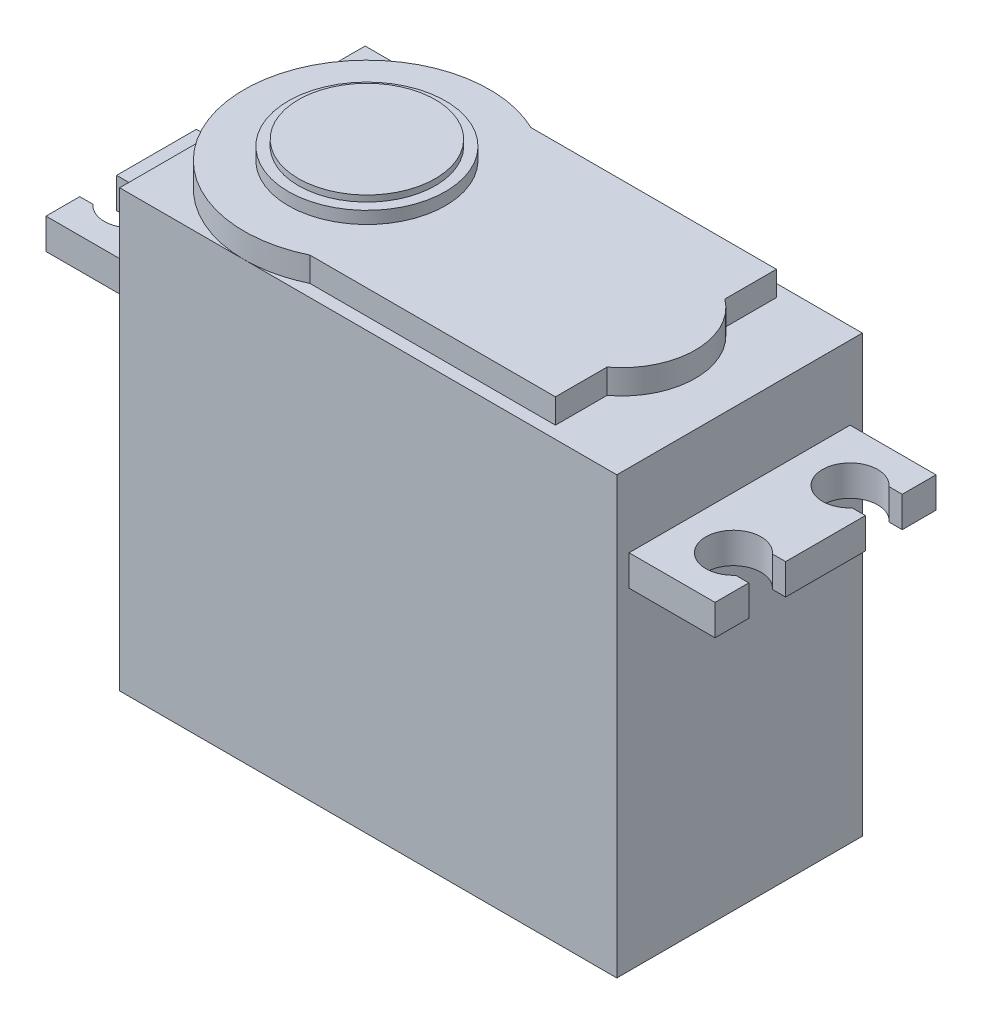
SolidWorks part; units mm, degrees
material "ABS"
ref_plane "Front" through (0, 0, 0) normal (0, 0, 1) x (1, 0, 0)
ref_plane "Top" through (0, 0, 0) normal (0, 1, 0) x (1, 0, 0)
ref_plane "Right" through (0, 0, 0) normal (1, 0, 0) x (0, 0, -1)
sketch "Sketch1" plane through (0, 0, 0) normal (0, 1, 0) x (1, 0, 0)
  line L0 (-20.25, 10) -> (20.25, -10) construction
  line L1 (-20.25, -10) -> (20.25, -10)
  line L2 (-20.25, -10) -> (-20.25, 10)
  line L3 (-20.25, 10) -> (20.25, 10)
  line L4 (20.25, -10) -> (20.25, 10)
  line L5 (20.25, 10) -> (-20.25, -10) construction
  dimension "D1" = 20
  dimension "D2" = 40.5
extrude "Boss-Extrude1" add sketch "Sketch1" along normal blind 35.5
sketch "Sketch2" plane through (0, 35.5, 0) normal (0, 1, 0) x (1, 0, 0)
  line L0 (-5.75, -9) -> (14.25, -9)
  line L1 (14.25, -9) -> (14.25, -4.8)
  line L2 (-5.75, 9) -> (14.25, 9)
  line L3 (14.25, 9) -> (14.25, 4.8)
  line L4 (20.25, 10) -> (-20.25, 10) construction
  line L5 (-20.25, -10) -> (20.25, -10) construction
  line L6 (20.25, -10) -> (20.25, 10) construction
  line L7 (20.25, -10) -> (20.25, 10) construction
  arc A0 (-5.75, 9) -> (-5.75, -9) centre (-10.1089, 0) ccw
  arc A1 (14.25, 4.8) -> (14.25, -4.8) centre (10.65, 0) cw
  point P6 (0, 10)
  point P12 (16.65, 0)
  point P13 (20.25, 0)
  dimension "D1" = 1
  dimension "D3" = 4.2
  dimension "D2" = 1
  dimension "D4" = 3.6
  dimension "D5" = 20
  dimension "D6" = 6
extrude "Boss-Extrude2" add sketch "Sketch2" along normal blind 2
sketch "Sketch3" plane through (0, 37.5, 0) normal (0, 1, 0) x (1, 0, 0)
  circle A0 centre (-10.1089, 0) radius 6.4
  arc A1 (-10.1089, 10) -> (-10.1089, -10) centre (-10.1089, 0) ccw construction
  dimension "D1" = 12.8
extrude "Boss-Extrude3" add sketch "Sketch3" along normal blind 1
sketch "Sketch4" plane through (0, 38.5, 0) normal (0, 1, 0) x (1, 0, 0)
  circle A0 centre (-10.1089, 0) radius 5.575
  circle A1 centre (-10.1089, 0) radius 6.4 construction
  dimension "D1" = 11.15
extrude "Boss-Extrude4" add sketch "Sketch4" along normal blind 0.5
ref_plane "Plane1" through (0, 29.5, 0) normal (0, 1, 0) x (1, 0, 0)
sketch "Sketch5" plane through (0, 29.5, 0) normal (0, 1, 0) x (1, 0, 0)
  line L0 (20.25, 9) -> (27.25, 9)
  line L1 (20.25, -10) -> (20.25, 10) construction
  line L2 (27.25, 0) -> (27.25, 3.25)
  line L3 (20.25, 0) -> (27.25, 0)
  line L4 (20.25, 0) -> (20.25, 9)
  line L5 (20.25, 10) -> (-10.1089, 10) construction
  line L7 (24.5, 7) -> (24.5, 9) construction
  line L8 (27.25, 6.25) -> (27.25, 9)
  line L9 (26.1771, 6.25) -> (27.25, 6.25)
  line L10 (26.1771, 3.25) -> (27.25, 3.25)
  arc A0 (26.1771, 6.25) -> (26.1771, 3.25) centre (24.5, 4.75) ccw
  point P9 (22.25, 4.75)
  dimension "D4" = 4.5
  dimension "D5" = 2
  dimension "D1" = 1
  dimension "D2" = 9
  dimension "D3" = 7
  dimension "D6" = 3
  dimension "D7" = 2
extrude "Boss-Extrude5" add sketch "Sketch5" against normal blind 2.5
mirror "Mirror1" about plane through (0, 0, 0) normal (1, 0, 0) of "Boss-Extrude5"
mirror "Mirror2" about plane through (0, 0, 0) normal (0, 0, 1) of "Boss-Extrude5", "Mirror1"
